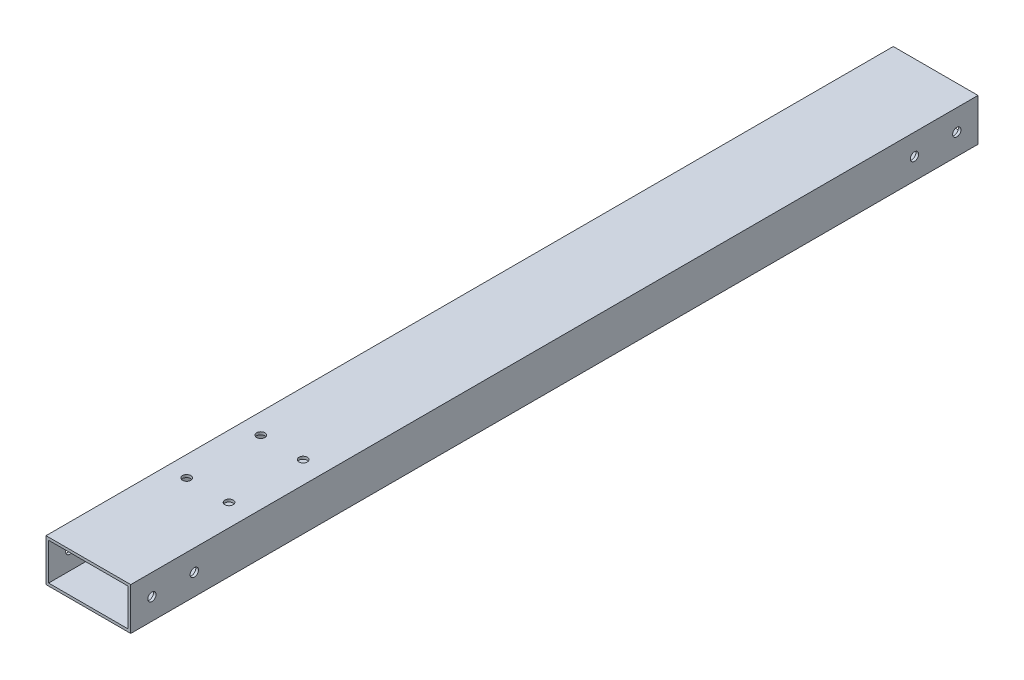
SolidWorks part; units mm, degrees
ref_plane "Front Plane" through (0, 0, 0) normal (0, 0, 1) x (1, 0, 0)
ref_plane "Top Plane" through (0, 0, 0) normal (0, 1, 0) x (1, 0, 0)
ref_plane "Right Plane" through (0, 0, 0) normal (1, 0, 0) x (0, 0, -1)
sketch "Sketch1" plane through (0, 0, 0) normal (0, 0, 1) x (1, 0, 0)
  line L0 (-23.8125, 11.1125) -> (23.8125, 11.1125)
  line L2 (-25.4, 12.7) -> (25.4, 12.7)
  line L3 (-25.4, 12.7) -> (-25.4, -12.7)
  line L4 (-25.4, -12.7) -> (25.4, -12.7)
  line L5 (25.4, 12.7) -> (25.4, -12.7)
  line L10 (23.8125, 11.1125) -> (23.8125, -11.1125)
  line L11 (-23.8125, -11.1125) -> (23.8125, -11.1125)
  line L12 (-23.8125, 11.1125) -> (-23.8125, -11.1125)
  point P12 (0, 12.7)
  point P14 (25.4, 0)
  dimension "Wall Thickness" = 1.5875
  dimension "Outside Width" = 50.8
  dimension "Outside Height" = 25.4
  dimension "Inside Height" = 22.225
  dimension "Inside Width" = 47.625
sketch "Sketch2" plane through (0, 0, 0) normal (1, 0, 0) x (0, 0, -1)
  line L0 (254, 0) -> (-254, 0)
  point P4 (0, 0)
  point P7 (-254, 0)
  point P10 (254, 0)
  dimension "Length" = 508
sketch "Sketch3" plane through (0, 0, 0) normal (0, 0, 1) x (1, 0, 0)
  line L21 (25.4, 12.7) -> (-25.4, 12.7)
  line L22 (25.4, -12.7) -> (25.4, 12.7)
  line L23 (-25.4, -12.7) -> (25.4, -12.7)
  line L24 (-25.4, 12.7) -> (-25.4, -12.7)
  line L25 (25.4, 12.7) -> (-25.4, 12.7)
  line L26 (25.4, -12.7) -> (25.4, 12.7)
  line L27 (-25.4, -12.7) -> (25.4, -12.7)
  line L28 (-25.4, 12.7) -> (-25.4, -12.7)
  line L29 (23.8125, 11.1125) -> (-23.8125, 11.1125)
  line L30 (23.8125, -11.1125) -> (23.8125, 11.1125)
  line L31 (-23.8125, -11.1125) -> (23.8125, -11.1125)
  line L32 (-23.8125, 11.1125) -> (-23.8125, -11.1125)
  line L33 (23.8125, 11.1125) -> (-23.8125, 11.1125)
  line L34 (23.8125, -11.1125) -> (23.8125, 11.1125)
  line L35 (-23.8125, -11.1125) -> (23.8125, -11.1125)
  line L36 (-23.8125, 11.1125) -> (-23.8125, -11.1125)
  dimension "D1" = 0
  dimension "D2" = 0
extrude "Boss-Extrude1" add sketch "Sketch3" along normal up to vertex (254 mm away) and the other way up to vertex (254 mm away) up to point (0, 0, 254) other way up to point (0, 0, -254)
sketch "Drawing Reference" plane through (0, 0, 0) normal (1, 0, 0) x (0, 0, -1)
  line L0 (-254, 0) -> (254, 0) construction
  line L1 (0, -12.7) -> (0, 12.7) construction
  line L2 (-254, -12.7) -> (254, -12.7) construction
  line L5 (-254, 12.7) -> (254, 12.7) construction
  point P7 (-217.424, 0)
  point P8 (217.424, 0)
  dimension "D1" = 36.576
hole_wizard "#10 Clearance Hole1" positions "Sketch4" profile "Sketch5" hole size "#10" standard "ANSI Inch" end condition through all
sketch "Sketch4" plane through (25.4, 0, 0) normal (1, 0, 0) x (0, 0, -1)
  point P0 (-241.3, 0)
  point P3 (-215.9, 0)
  point P6 (215.9, 0)
  point P9 (241.3, 0)
sketch "Sketch5" plane through (25.4, 0, 241.3) normal (0, 1, 0) x (0, 0, -1)
  line L0 (0, 0) -> (0, 50.8)
  line L1 (0, 50.8) -> (2.4892, 50.8)
  line L2 (2.4892, 50.8) -> (2.4892, 0)
  line L5 (2.4892, 0) -> (0, 0)
  line L11 (0, -6.35) -> (0, 107.95) construction
  dimension "Thru Hole Dia." = 4.9784
  dimension "Thru Hole Depth" = 50.8
sketch "Sketch6" plane through (0, 12.7, 0) normal (0, 1, 0) x (1, 0, 0)
  line L0 (-13.208, -137.3969) -> (-13.208, -181.8469) construction
  line L1 (-13.208, -181.8469) -> (12.192, -181.8469) construction
  line L2 (12.192, -181.8469) -> (12.192, -137.3969) construction
  line L3 (12.192, -137.3969) -> (-13.208, -137.3969) construction
hole_wizard "#10 Clearance Hole2" positions "Sketch9" profile "Sketch10" hole size "#10" standard "ANSI Inch" end condition through all
sketch "Sketch9" plane through (0, 12.7, 0) normal (0, 1, 0) x (1, 0, 0)
  point P0 (12.192, -137.3969)
  point P3 (-13.208, -137.3969)
  point P6 (-13.208, -181.8469)
  point P9 (12.192, -181.8469)
sketch "Sketch10" plane through (12.192, 12.7, 137.3969) normal (1, 0, 0) x (0, 0, 1)
  line L0 (0, 0) -> (0, 25.4)
  line L1 (0, 25.4) -> (2.4892, 25.4)
  line L2 (2.4892, 25.4) -> (2.4892, 0)
  line L5 (2.4892, 0) -> (0, 0)
  line L11 (0, -6.35) -> (0, 107.95) construction
  dimension "Thru Hole Dia." = 4.9784
  dimension "Thru Hole Depth" = 25.4
equation "\"D1@Drawing Reference\"=\"Outside Width@Sketch1\" * 0.72"
